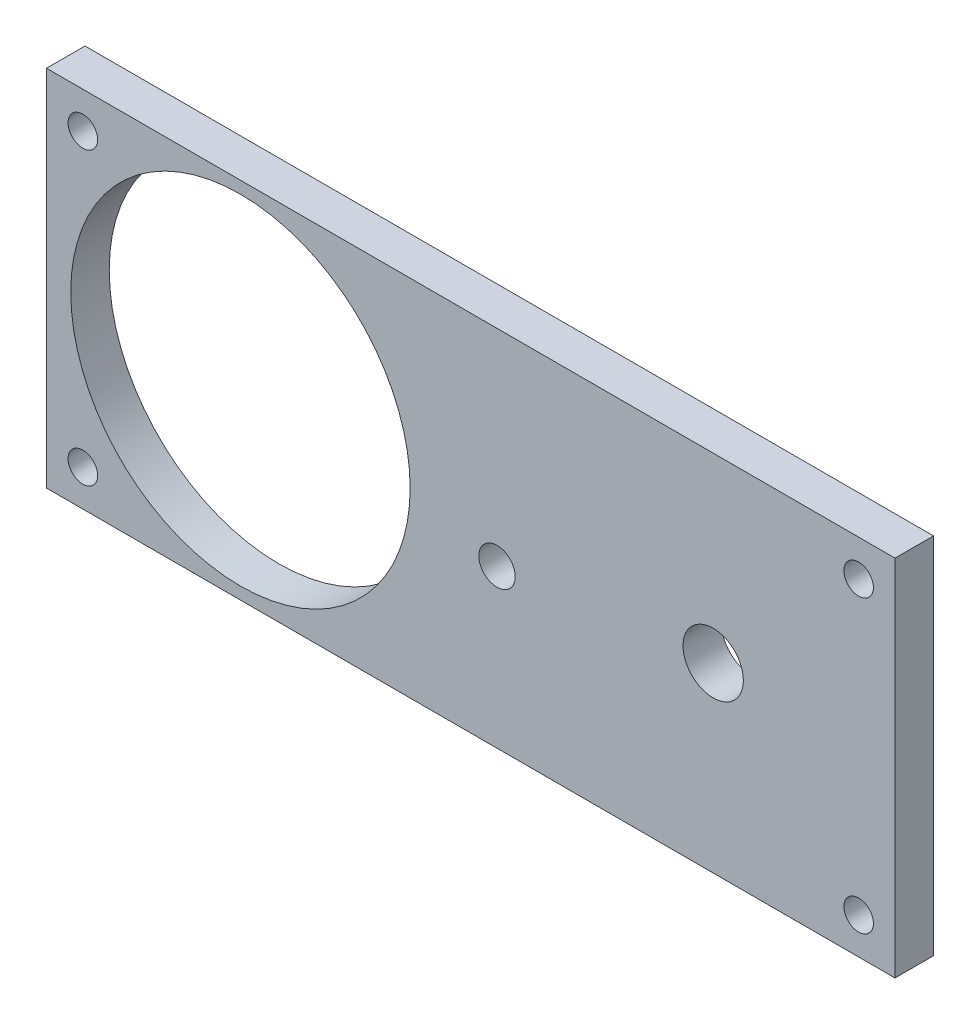
SolidWorks part; units mm, degrees
ref_plane "Front Plane" through (0, 0, 0) normal (0, 0, 1) x (1, 0, 0)
ref_plane "Top Plane" through (0, 0, 0) normal (0, 1, 0) x (1, 0, 0)
ref_plane "Right Plane" through (0, 0, 0) normal (1, 0, 0) x (0, 0, -1)
sketch "Sketch1" plane through (0, 0, 0) normal (0, 0, 1) x (1, 0, 0)
  line L0 (70, 15) -> (0, 15) construction
  line L1 (0, 0) -> (70, 0)
  line L2 (0, 0) -> (0, 30)
  line L3 (0, 30) -> (70, 30)
  line L4 (70, 0) -> (70, 30)
  circle A0 centre (55, 15) radius 2.4892
  circle A1 centre (37.1667, 13) radius 1.4986
  circle A2 centre (25.1698, 20.9334) radius 0.9906 construction
  circle A3 centre (37.1667, 13) radius 11.4777 construction
  circle A4 centre (25.1698, 20.9334) radius 7.1501 construction
  circle A5 centre (55, 15) radius 12.827 construction
  circle A6 centre (16, 15) radius 14
  circle A7 centre (37.1667, 13) radius 5.1181 construction
  point P7 (55, 15)
  point P8 (37.1667, 13)
  point P9 (25.1698, 20.9334)
  point P19 (16, 15)
  dimension "D6" = 4.9784
  dimension "D7" = 2.9972
  dimension "D8" = 1.9812
  dimension "D9" = 25.654
  dimension "D10" = 22.9553
  dimension "D11" = 14.3002
  dimension "D13" = 28
  dimension "D14" = 10.2362
  dimension "D1" = 17.9451
  dimension "D2" = 14.3828
  dimension "D3" = 30
  dimension "D4" = 70
  dimension "D5" = 15
  dimension "D12" = 10.922
  dimension "D15" = 16
  dimension "D16" = 13
extrude "Boss-Extrude2" add sketch "Sketch1" along normal blind 3.175
hole_wizard "#2 Clearance Hole1" positions "Sketch4" profile "Sketch3" hole size "#2" standard "ANSI Inch" end condition through all
sketch "Sketch4" plane through (0, 0, 3.175) normal (0, 0, 1) x (1, 0, 0)
  line L0 (67, 0) -> (67, 30) construction
  line L1 (0, 0) -> (70, 0) construction
  line L2 (70, 30) -> (0, 30) construction
  line L4 (70, 0) -> (70, 30) construction
  line L5 (3, 30) -> (3, 0) construction
  line L7 (0, 30) -> (0, 0) construction
  point P8 (67, 3)
  point P10 (67, 27)
  point P27 (3, 27)
  point P29 (3, 3)
  dimension "D1" = 3
  dimension "D2" = 3
  dimension "D3" = 3
  dimension "D4" = 3
  dimension "D5" = 3
  dimension "D6" = 3
sketch "Sketch3" plane through (67, 3, 3.175) normal (1, 0, 0) x (0, -1, 0)
  line L0 (0, 0) -> (0, 3.175)
  line L1 (0, 3.175) -> (1.2192, 3.175)
  line L2 (1.2192, 3.175) -> (1.2192, 0)
  line L5 (1.2192, 0) -> (0, 0)
  line L11 (0, -6.35) -> (0, 107.95) construction
  dimension "Thru Hole Dia." = 2.4384
  dimension "Thru Hole Depth" = 3.175
